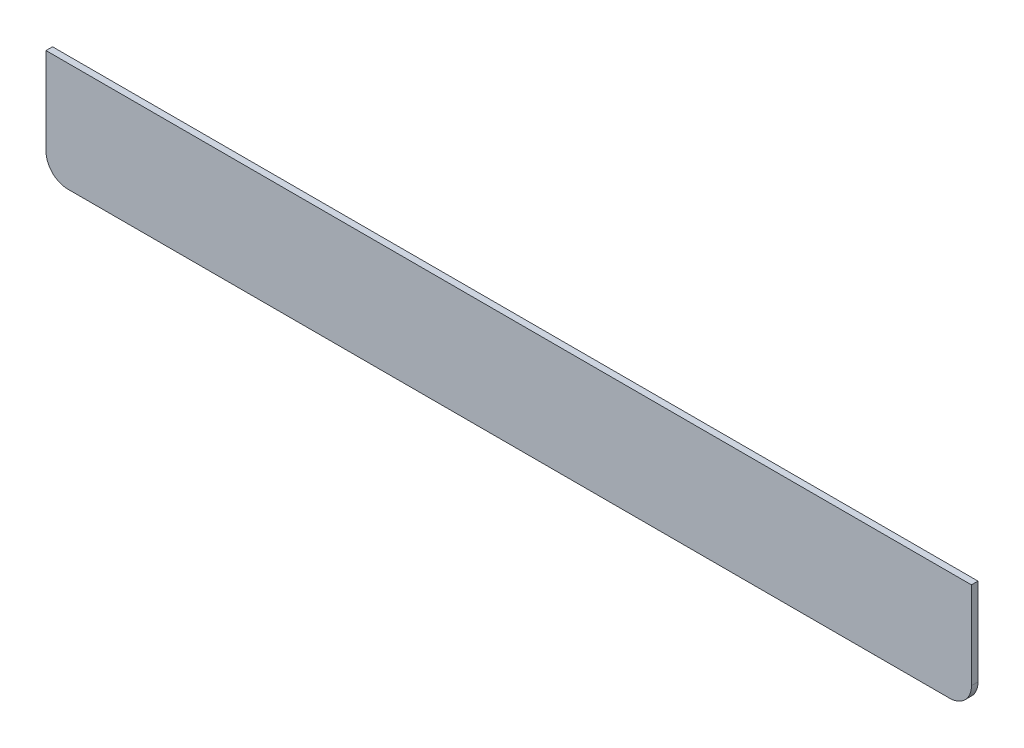
SolidWorks part; units mm, degrees
material "AISI 304"
ref_plane "Спереди" through (0, 0, 0) normal (0, 0, 1) x (1, 0, 0)
ref_plane "Сверху" through (0, 0, 0) normal (0, 1, 0) x (1, 0, 0)
ref_plane "Справа" through (0, 0, 0) normal (1, 0, 0) x (0, 0, -1)
other "Configuration Table"
sketch "Эскиз1" plane through (0, 0, 0) normal (0, 0, 1) x (1, 0, 0)
  line L1 (-212, -25) -> (212, -25)
  line L2 (-212, -25) -> (-212, 25)
  line L3 (-212, 25) -> (212, 25)
  line L4 (212, -25) -> (212, 25)
  line L5 (-212, -25) -> (212, 25) construction
  line L6 (-212, 25) -> (212, -25) construction
  point P0 (0, 0)
  dimension "D1" = 50
  dimension "D2" = 424
extrude "Бобышка-Вытянуть1" add sketch "Эскиз1" along normal blind 3
fillet "Скругление1" radius 10 2 edges at (212, -25, 1.5) (-212, -25, 1.5)
